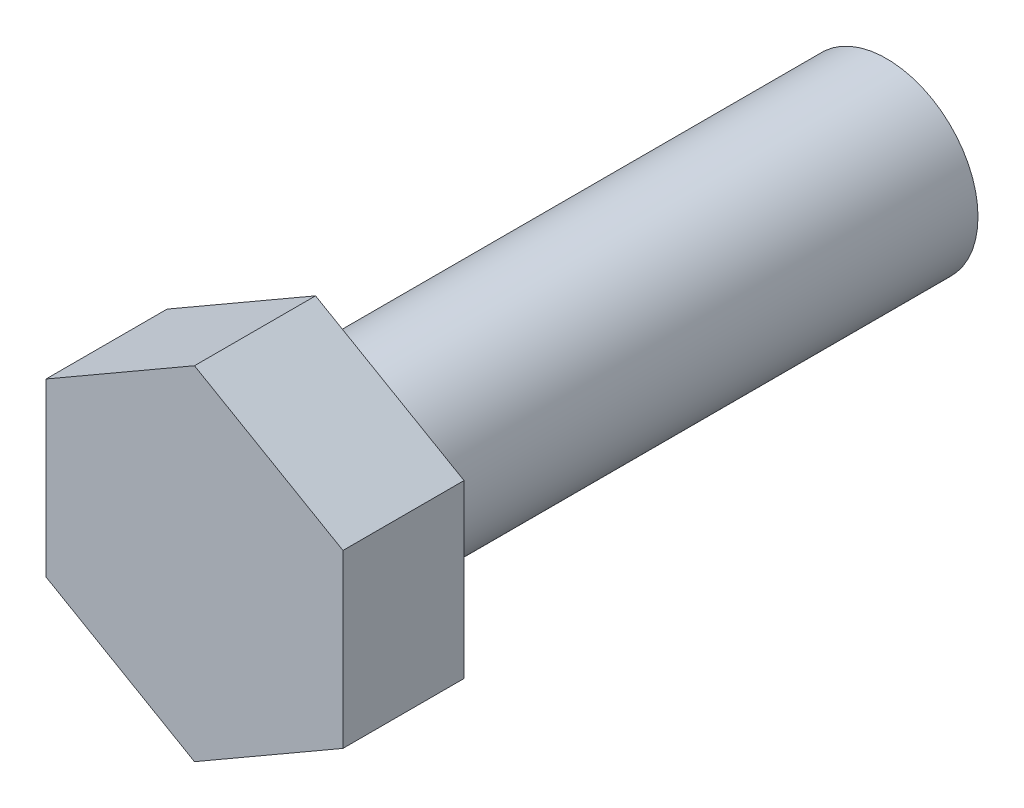
SolidWorks part; units mm, degrees
material "Простая углеродистая сталь"
ref_plane "Спереди" through (0, 0, 0) normal (0, 0, 1) x (1, 0, 0)
ref_plane "Сверху" through (0, 0, 0) normal (0, 1, 0) x (1, 0, 0)
ref_plane "Справа" through (0, 0, 0) normal (1, 0, 0) x (0, 0, -1)
sketch "Эскиз1" plane through (0, 0, 0) normal (0, 0, 1) x (1, 0, 0)
  line L1 (0, 7.5056) -> (-6.5, 3.7528)
  line L2 (-6.5, 3.7528) -> (-6.5, -3.7528)
  line L3 (-6.5, -3.7528) -> (0, -7.5056)
  line L4 (0, -7.5056) -> (6.5, -3.7528)
  line L5 (6.5, -3.7528) -> (6.5, 3.7528)
  line L6 (6.5, 3.7528) -> (0, 7.5056)
  circle A0 centre (0, 0) radius 6.5 construction
  dimension "S" = 13
extrude "Бобышка-Вытянуть1" add sketch "Эскиз1" along normal blind 5.3
sketch "Эскиз3" plane through (0, 0, 0) normal (0, 0, -1) x (-1, 0, 0)
  circle A0 centre (0, 0) radius 4
  dimension "d" = 8
extrude "Бобышка-Вытянуть2" add sketch "Эскиз3" along normal blind 25
